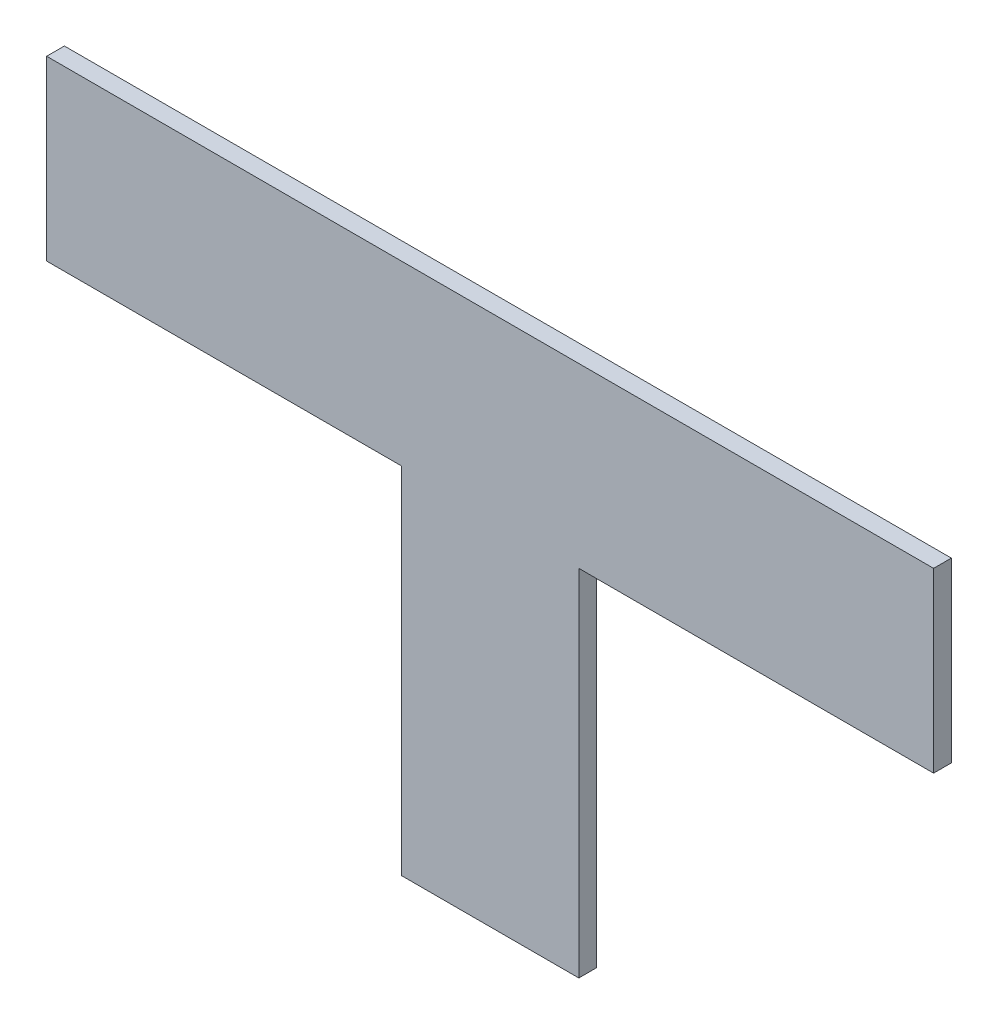
SolidWorks part; units mm, degrees
ref_plane "Front Plane" through (0, 0, 0) normal (0, 0, 1) x (1, 0, 0)
ref_plane "Top Plane" through (0, 0, 0) normal (0, 1, 0) x (1, 0, 0)
ref_plane "Right Plane" through (0, 0, 0) normal (1, 0, 0) x (0, 0, -1)
sketch "Sketch1" plane through (0, 0, 0) normal (0, 0, 1) x (1, 0, 0)
  line L1 (-10, -20) -> (10, -20)
  line L2 (-10, -20) -> (-10, 20)
  line L3 (-10, 20) -> (10, 20)
  line L4 (10, -20) -> (10, 20)
  line L5 (-10, -20) -> (10, 20) construction
  line L6 (-10, 20) -> (10, -20) construction
  line L7 (-50, 40) -> (50, 40)
  line L8 (-50, 40) -> (-50, 20)
  line L9 (-50, 20) -> (50, 20)
  line L10 (50, 40) -> (50, 20)
  point P0 (0, 0)
  dimension "D1" = 20
  dimension "D2" = 40
  dimension "D3" = 0
  dimension "D4" = 40
  dimension "D5" = 100
  dimension "D6" = 20
extrude "Boss-Extrude1" add sketch "Sketch1" along normal blind 2 contours L10 L7 L8 L9 L3 | L1 L4 L3 L2
